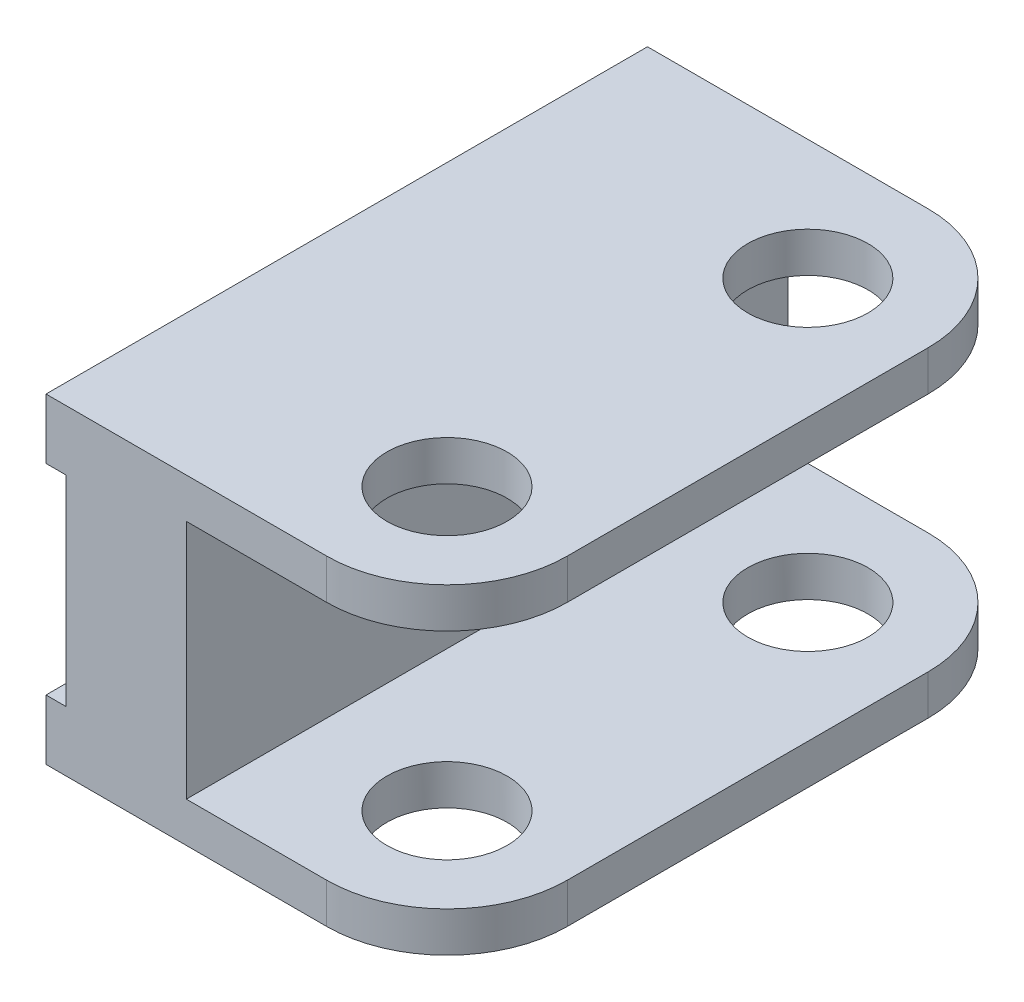
SolidWorks part; units mm, degrees
ref_plane "Front Plane" through (0, 0, 0) normal (0, 0, 1) x (1, 0, 0)
ref_plane "Top Plane" through (0, 0, 0) normal (0, 1, 0) x (1, 0, 0)
ref_plane "Right Plane" through (0, 0, 0) normal (1, 0, 0) x (0, 0, -1)
sketch "Sketch1" plane through (0, 0, 0) normal (0, 0, 1) x (1, 0, 0)
  line L1 (0, 0) -> (35, 0)
  line L2 (0, 0) -> (0, 80)
  line L3 (0, 80) -> (35, 80)
  line L4 (35, 10) -> (35, 70)
  line L5 (35, 80) -> (100, 80)
  line L7 (35, 70) -> (100, 70)
  line L8 (100, 80) -> (100, 70)
  line L9 (35, 0) -> (100, 0)
  line L11 (35, 10) -> (100, 10)
  line L12 (100, 0) -> (100, 10)
  point P11 (0, 0)
  point P12 (0, 0)
  dimension "D1" = 35
  dimension "D2" = 10
  dimension "D3" = 10
  dimension "D4" = 80
  dimension "D5" = 100
extrude "Boss-Extrude1" add sketch "Sketch1" along normal blind 150
sketch "Sketch2" plane through (0, 0, 150) normal (0, 0, 1) x (1, 0, 0)
  line L1 (0, 40) -> (35, 40) construction
  line L2 (0, 80) -> (0, 0) construction
  line L3 (35, 10) -> (35, 70) construction
  line L5 (0, 65) -> (5, 65)
  line L6 (0, 65) -> (0, 15)
  line L7 (0, 15) -> (5, 15)
  line L8 (5, 65) -> (5, 15)
  point P10 (0, 40)
  dimension "D1" = 50
  dimension "D2" = 5
extrude "Cut-Extrude1" cut sketch "Sketch2" against normal blind 150
sketch "Sketch3" plane through (0, 80, 0) normal (0, 1, 0) x (1, 0, 0)
  line L0 (100, 0) -> (0, 0) construction
  circle A0 centre (70, -30) radius 15
  circle A1 centre (70, -120) radius 15
  dimension "D3" = 30
  dimension "D4" = 30
  dimension "D1" = 30
  dimension "D2" = 70
  dimension "D5" = 30
extrude "Cut-Extrude2" cut sketch "Sketch3" against normal blind 150
fillet "Fillet1" radius 30 4 edges at (100, 75, 0) (100, 5, 0) (100, 5, 150) (100, 75, 150)
